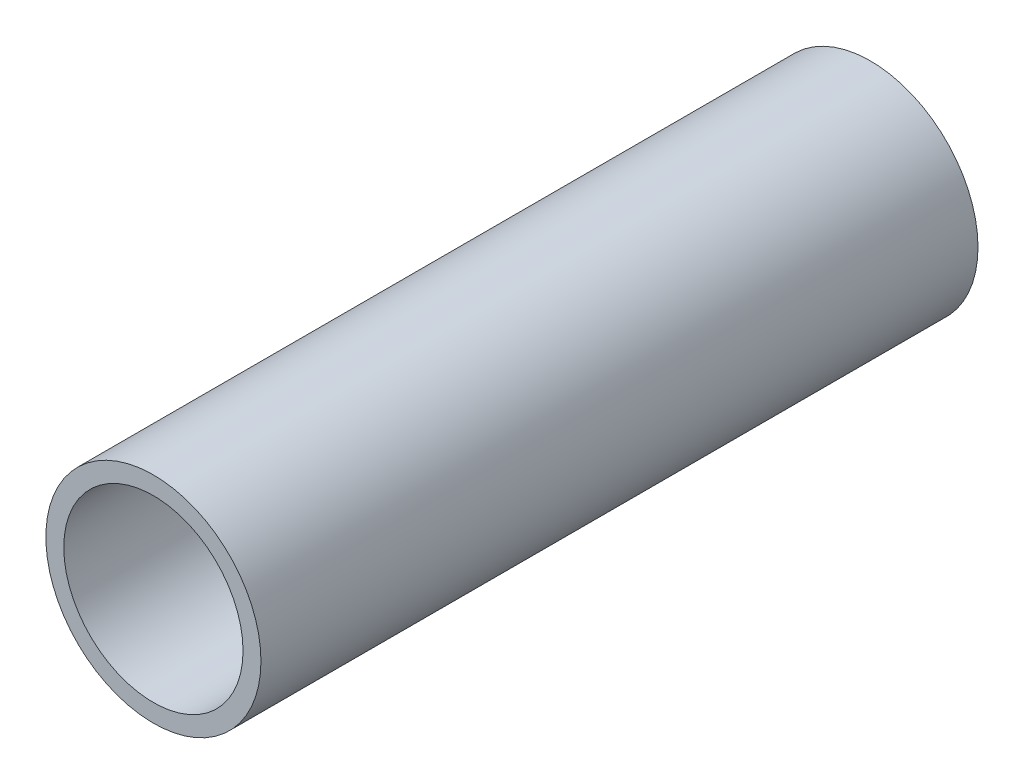
SolidWorks part; units mm, degrees
ref_plane "前视基准面" through (0, 0, 0) normal (0, 0, 1) x (1, 0, 0)
ref_plane "上视基准面" through (0, 0, 0) normal (0, 1, 0) x (1, 0, 0)
ref_plane "右视基准面" through (0, 0, 0) normal (1, 0, 0) x (0, 0, -1)
sketch "草图1" plane through (0, 0, 0) normal (0, 0, 1) x (1, 0, 0)
  circle A0 centre (0, 0) radius 6
  circle A1 centre (0, 0) radius 5
  dimension "D1" = 12
  dimension "D2" = 10
extrude "凸台-拉伸1" add sketch "草图1" along normal blind 40
